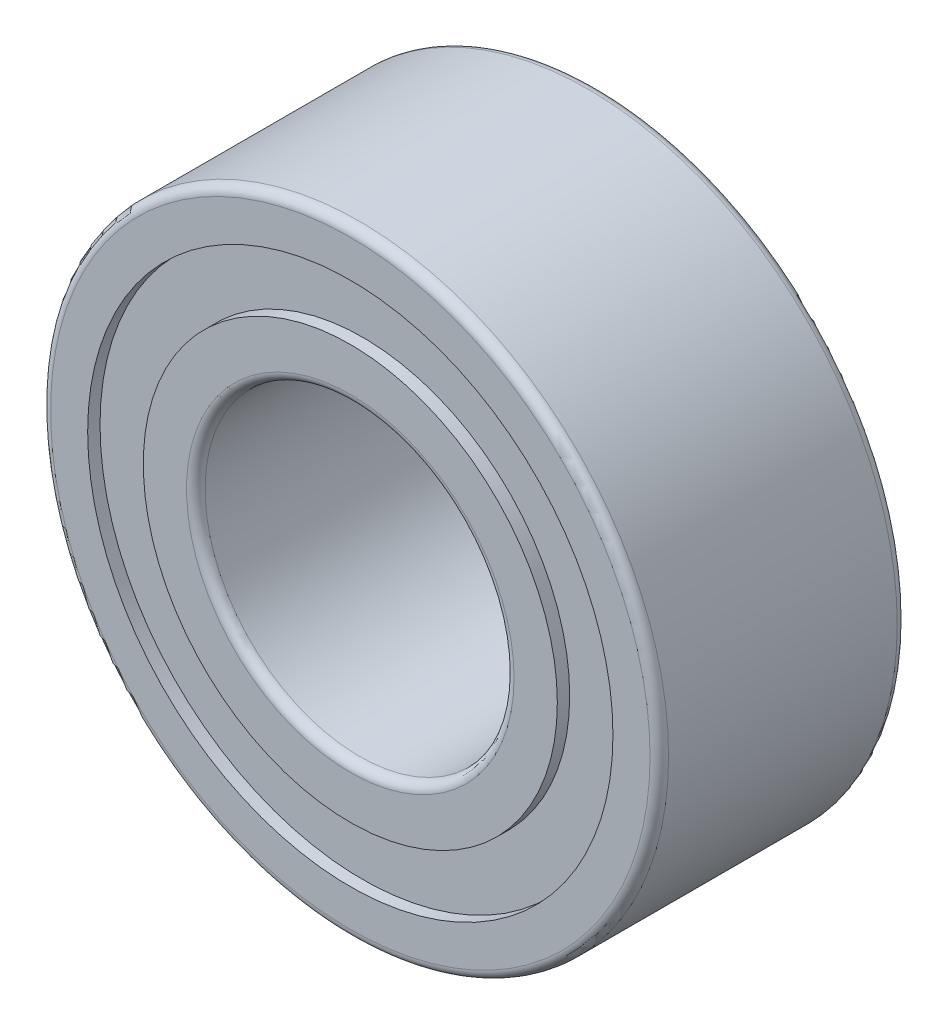
SolidWorks part; units mm, degrees
ref_plane "前视基准面" through (0, 0, 0) normal (0, 0, 1) x (1, 0, 0)
ref_plane "上视基准面" through (0, 0, 0) normal (0, 1, 0) x (1, 0, 0)
ref_plane "右视基准面" through (0, 0, 0) normal (1, 0, 0) x (0, 0, -1)
sketch "草图1" plane through (0, 0, 0) normal (0, 0, 1) x (1, 0, 0)
  circle A0 centre (0, 0) radius 2.5
  circle A1 centre (0, 0) radius 5
  dimension "D1" = 5
  dimension "D2" = 10
extrude "拉伸1" add sketch "草图1" along normal mid plane 4
sketch "草图2" plane through (0, 0, 2) normal (0, 0, 1) x (1, 0, 0)
  circle A0 centre (0, 0) radius 3.35
  circle A1 centre (0, 0) radius 4.25
  dimension "D1" = 6.7
  dimension "D2" = 8.5
extrude "拉伸2" cut sketch "草图2" against normal blind 0.2
mirror "镜向1" about plane through (0, 0, 0) normal (0, 0, 1) of "拉伸2"
fillet "圆角1" radius 0.15 4 edges at (2.5, 0, -2) (5, 0, -2) (2.5, 0, 2) (5, 0, 2)
